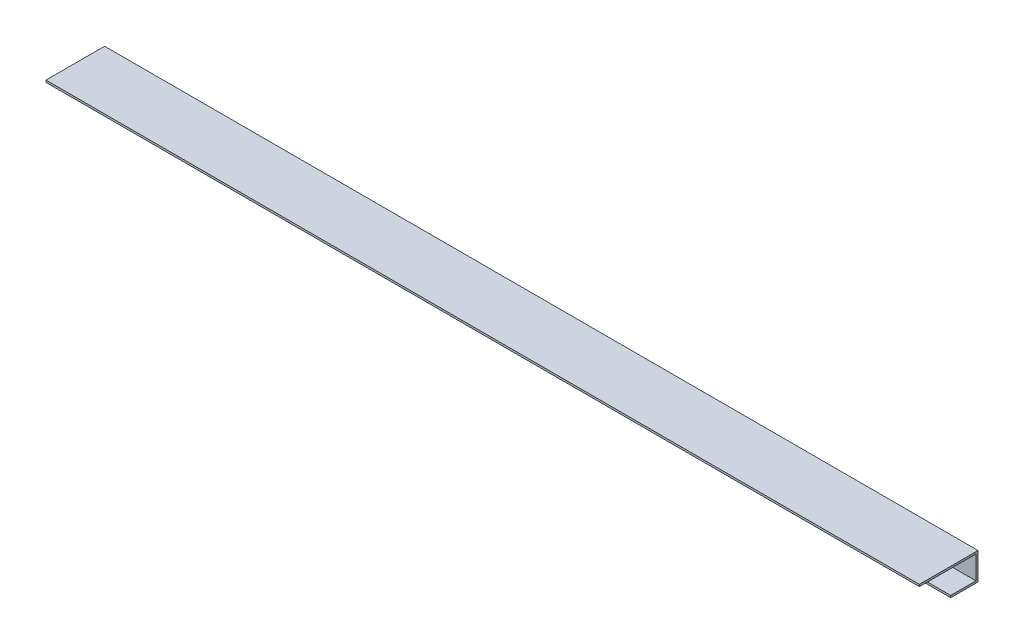
SolidWorks part; units mm, degrees
ref_plane "Front Plane" through (0, 0, 0) normal (0, 0, 1) x (1, 0, 0)
ref_plane "Top Plane" through (0, 0, 0) normal (0, 1, 0) x (1, 0, 0)
ref_plane "Right Plane" through (0, 0, 0) normal (1, 0, 0) x (0, 0, -1)
sketch "Sketch1" plane through (0, 0, 0) normal (1, 0, 0) x (0, 0, -1)
  line L0 (0, 0) -> (58, 0)
  line L1 (58, 0) -> (58, -27)
  line L2 (58, -27) -> (31, -27)
  line L3 (0, -2) -> (56, -2)
  line L4 (56, -2) -> (56, -25)
  line L5 (56, -25) -> (31, -25)
  line L6 (0, 0) -> (0, -2)
  line L7 (31, -25) -> (31, -27)
  dimension "D1" = 2
  dimension "D2" = 58
  dimension "D3" = 27
  dimension "D4" = 27
extrude "Boss-Extrude1" add sketch "Sketch1" along normal blind 864
equation "\"door_base_short7_R1_R_open_Single_width\"=864"
equation "\"D1@Boss-Extrude1\"= \"door_base_short7_L1_R_open_Single_width\""
equation "\"CarBeamWidth\"=700.0"
equation "\"WheelWidth\"=650.0"
equation "\"Wheel_FrontBoxDistance\"=1390.0"
equation "\"MetalSheet_3mm_length\"=5030.0"
equation "\"MetalSheet_3mm_width\"=1923.0"
equation "\"MetalSheet_3mm_FloorCut_L_length\"=1764.0"
equation "\"MetalSheet_3mm_FloorCut_L_disdance\"=1665.0"
equation "\"MetalSheet_3mm_FloorCut_R_length\"=1764.0"
equation "\"MetalSheet_3mm_FloorCut_R_disdance\"=1665.0"
equation "\"indoorHeight\"=1940.0"
equation "\"haveDoor_R\"=1"
equation "\"side_door_bottom_R_3mm_length\"=1934.0"
equation "\"1Bar_Side_RF_3mm_length\"=1493.0"
equation "\"1Bar_Side_RB_3mm_length\"=1493.0"
equation "\"DoorSeparator_RF_3mm_withHinge_toFrontDistance\"=1673.0"
equation "\"DoorSeparator_RF_3mm_withHinge_exist\"=1"
equation "\"DoorSeparator_RB_3mm_withHinge_toFrontDistance\"=3427.0"
equation "\"DoorSeparator_RB_3mm_withHinge_exist\"=1"
equation "\"Door_R1_L_open_Single_toFrontDistance\"=2547.5"
equation "\"Door_R1_L_open_Single_exist\"=1"
equation "\"door_base_long7_R1_L_open_Single_height\"=1890.0"
equation "\"door_base_short7_R1_L_open_Single_height\"=1890.0"
equation "\"door_base_short7_R1_L_open_Single_width\"=864"
equation "\"Door_R1_R_open_Single_toFrontDistance\"=3422.0"
equation "\"Door_R1_R_open_Single_exist\"=1"
equation "\"door_base_long7_R1_R_open_Single_height\"=1890.0"
equation "\"door_base_short7_R1_R_open_Single_height\"=1890.0"
equation "\"x\"=66.0"
equation "\"da\"=62.0"
equation "\"SquareTube_length\"=1923.0"
equation "\"channelSteel_length\"=5030.0"
equation "\"SquareTube_inFront_AvgDistance\"=285.0"
equation "\"SquareTube_inFront_TotalCount\"=5"
equation "\"SquareTube_inFront1_cutDepth50_R\"=0.5"
equation "\"SquareTube_inFront1_cutDepth50_L\"=0.5"
equation "\"SquareTube_inFront2_cutDepth50_R\"=0.5"
equation "\"SquareTube_inFront2_cutDepth50_L\"=0.5"
equation "\"SquareTube_inFront3_cutDepth50_R\"=0.5"
equation "\"SquareTube_inFront3_cutDepth50_L\"=0.5"
equation "\"SquareTube_inFront4_cutDepth50_R\"=0.5"
equation "\"SquareTube_inFront4_cutDepth50_L\"=0.5"
equation "\"SquareTube_inFront5_cutDepth50_R\"=50"
equation "\"SquareTube_inFront5_cutDepth50_L\"=50"
equation "\"SquareTube_inFront6_cutDepth50_R\"=50"
equation "\"SquareTube_inFront6_cutDepth50_L\"=50"
equation "\"SquareTube_inFront7_cutDepth50_R\"=50"
equation "\"SquareTube_inFront7_cutDepth50_L\"=50"
equation "\"SquareTube_inFront8_cutDepth50_R\"=50"
equation "\"SquareTube_inFront8_cutDepth50_L\"=50"
equation "\"SquareTube_inFront9_cutDepth50_R\"=50"
equation "\"SquareTube_inFront9_cutDepth50_L\"=50"
equation "\"SquareTube_inFront10_cutDepth50_R\"=50"
equation "\"SquareTube_inFront10_cutDepth50_L\"=50"
equation "\"SquareTube_inFront11_cutDepth50_R\"=50"
equation "\"SquareTube_inFront11_cutDepth50_L\"=50"
equation "\"SquareTube_inFront12_cutDepth50_R\"=50"
equation "\"SquareTube_inFront12_cutDepth50_L\"=50"
equation "\"SquareTube_inFront13_cutDepth50_R\"=50"
equation "\"SquareTube_inFront13_cutDepth50_L\"=50"
equation "\"SquareTube_inFront14_cutDepth50_R\"=50"
equation "\"SquareTube_inFront14_cutDepth50_L\"=50"
equation "\"SquareTube_inBack_AvgDistance\"=333.125"
equation "\"SquareTube_inBack_TotalCount\"=9"
equation "\"SquareTube_inBack1_cutDepth50_R\"=50"
equation "\"SquareTube_inBack1_cutDepth50_L\"=50"
equation "\"SquareTube_inBack2_cutDepth50_R\"=50"
equation "\"SquareTube_inBack2_cutDepth50_L\"=50"
equation "\"SquareTube_inBack3_cutDepth50_R\"=50"
equation "\"SquareTube_inBack3_cutDepth50_L\"=50"
equation "\"SquareTube_inBack4_cutDepth50_R\"=50"
equation "\"SquareTube_inBack4_cutDepth50_L\"=50"
equation "\"SquareTube_inBack5_cutDepth50_R\"=50"
equation "\"SquareTube_inBack5_cutDepth50_L\"=50"
equation "\"SquareTube_inBack6_cutDepth50_R\"=0.5"
equation "\"SquareTube_inBack6_cutDepth50_L\"=0.5"
equation "\"SquareTube_inBack7_cutDepth50_R\"=0.5"
equation "\"SquareTube_inBack7_cutDepth50_L\"=0.5"
equation "\"SquareTube_inBack8_cutDepth50_R\"=0.5"
equation "\"SquareTube_inBack8_cutDepth50_L\"=0.5"
equation "\"boxLength\"=5100.0"
equation "\"boxWidth\"=1930.0"
equation "\"indoorHeight_para\"=25.0"
equation "\"rearLightHeight_para\"=265.0"
equation "\"doorColumnBar_A_FR_3mm_length_Cut\"=2310.0"
equation "\"A\"=0.0"
equation "\"side_door_bottom_R_3mm_toFrontDistance\"=1583.0"
equation "\"door_base_double_BL_height\"=1890.0"
equation "\"door_base_short7_BL_Single_height\"=1890.0"
equation "\"door_base_short7_BL_Single_width\"=864"
equation "\"door_base_long7_BR_Single_height\"=1890.0"
equation "\"door_base_short7_BR_Single_height\"=1890.0"
equation "\"door_base_short7_BR_Single_width\"=864"
equation "\"doorColumnBar_A_FL_3mm_length_Cut\"=2310.0"
equation "\"B\"=0.0"
equation "\"haveDoor_L\"=1"
equation "\"side_door_bottom_L_3mm_length\"=1934.0"
equation "\"side_door_bottom_L_3mm_toFrontDistance\"=1583.0"
equation "\"1Bar_Side_LF_3mm_length\"=1493.0"
equation "\"1Bar_Side_LB_3mm_length\"=1493.0"
equation "\"DoorSeparator_LF_3mm_withHinge_toFrontDistance\"=1673.0"
equation "\"DoorSeparator_LF_3mm_withHinge_exist\"=1"
equation "\"DoorSeparator_LB_3mm_withHinge_toFrontDistance\"=3427.0"
equation "\"DoorSeparator_LB_3mm_withHinge_exist\"=1"
equation "\"Door_L1_L_open_Single_toFrontDistance\"=3422.0"
equation "\"Door_L1_L_open_Single_exist\"=1"
equation "\"door_base_long7_L1_L_open_Single_height\"=1890.0"
equation "\"door_base_short7_L1_L_open_Single_height\"=1890.0"
equation "\"door_base_short7_L1_L_open_Single_width\"=864"
equation "\"Door_L1_R_open_Single_toFrontDistance\"=2547.5"
equation "\"Door_L1_R_open_Single_exist\"=1"
equation "\"door_base_long7_L1_R_open_Single_height\"=1890.0"
equation "\"door_base_short7_L1_R_open_Single_height\"=1890.0"
equation "\"door_base_short7_L1_R_open_Single_width\"=864"
